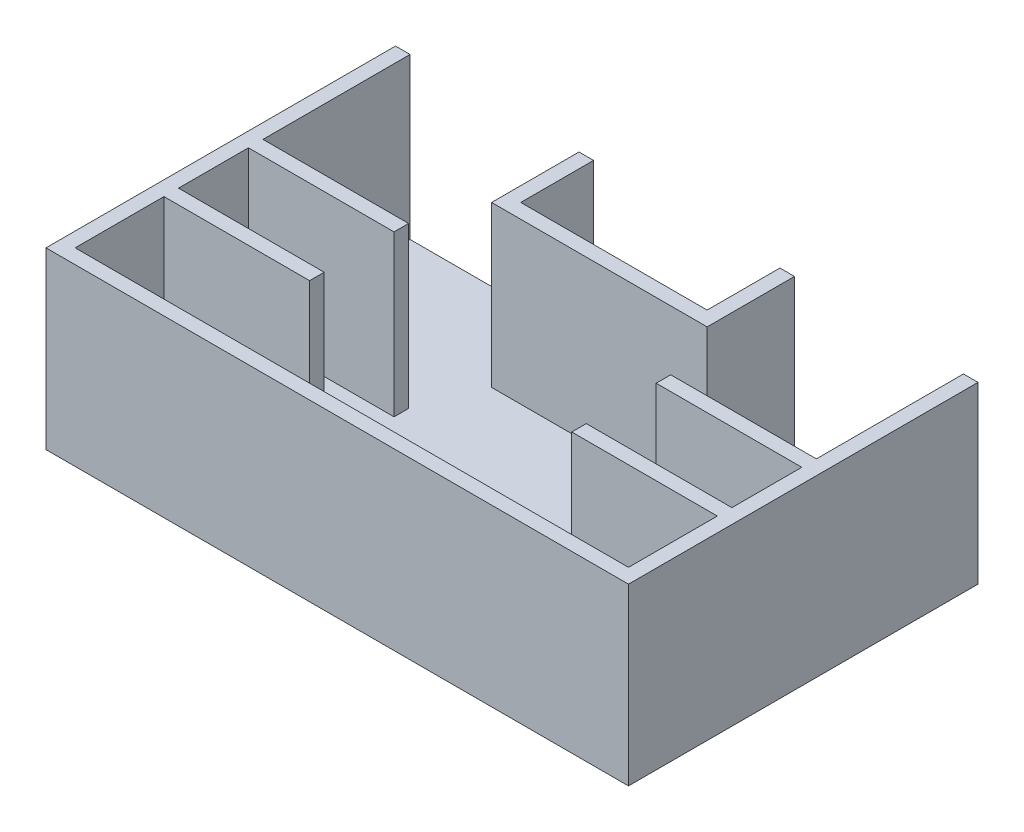
SolidWorks part; units mm, degrees
ref_plane "Front Plane" through (0, 0, 0) normal (0, 0, 1) x (1, 0, 0)
ref_plane "Top Plane" through (0, 0, 0) normal (0, 1, 0) x (1, 0, 0)
ref_plane "Right Plane" through (0, 0, 0) normal (1, 0, 0) x (0, 0, -1)
sketch "Sketch2" plane through (0, 0, 0) normal (0, 1, 0) x (1, 0, 0)
  line L1 (50, 50) -> (-50, 50)
  line L2 (50, 50) -> (50, -50)
  line L3 (50, -50) -> (-50, -50)
  line L4 (-50, 50) -> (-50, -50)
  line L5 (50, 50) -> (-50, -50) construction
  line L6 (50, -50) -> (-50, 50) construction
  point P0 (0, 0)
  dimension "D1" = 100
  dimension "D2" = 100
extrude "Boss-Extrude1" add sketch "Sketch2" along normal blind 2.5
sketch "Sketch4" plane through (0, 2.5, 0) normal (0, 1, 0) x (1, 0, 0)
  line L0 (-22.5, -17.75) -> (-22.5, -29.75) construction
  line L1 (-47.5, -47.5) -> (47.5, -47.5)
  line L2 (-47.5, -47.5) -> (-47.5, -32.25)
  line L3 (-47.5, 47.5) -> (-18.5, 47.5)
  line L4 (47.5, -47.5) -> (47.5, -32.25)
  line L5 (-47.5, 47.5) -> (47.5, -47.5) construction
  line L6 (-47.5, -23.75) -> (47.5, -23.75) construction
  line L7 (-47.5, -15.25) -> (-22.5, -15.25)
  line L8 (-47.5, -17.75) -> (-22.5, -17.75)
  line L9 (-22.5, -15.25) -> (-22.5, -17.75)
  line L10 (-22.5, -29.75) -> (-47.5, -29.75)
  line L11 (-22.5, -29.75) -> (-22.5, -32.25)
  line L12 (-50, 50) -> (-50, -50)
  line L13 (-50, -50) -> (50, -50)
  line L14 (50, -50) -> (50, 50)
  line L15 (50, 50) -> (-50, 50)
  line L16 (-50, 50) -> (-50, -50)
  line L17 (-50, -50) -> (50, -50)
  line L18 (50, -50) -> (50, 50)
  line L19 (50, 50) -> (16, 50)
  line L20 (-22.5, -32.25) -> (-47.5, -32.25)
  line L21 (-47.5, -29.75) -> (-47.5, -17.75)
  line L22 (-47.5, -15.25) -> (-47.5, 47.5)
  line L23 (0, -50) -> (0, 75) construction
  line L24 (47.5, -17.75) -> (22.5, -17.75)
  line L25 (47.5, -15.25) -> (22.5, -15.25)
  line L26 (22.5, -15.25) -> (22.5, -17.75)
  line L27 (22.5, -29.75) -> (47.5, -29.75)
  line L28 (22.5, -29.75) -> (22.5, -32.25)
  line L29 (22.5, -32.25) -> (47.5, -32.25)
  line L30 (47.5, -29.75) -> (47.5, -17.75)
  line L31 (47.5, -15.25) -> (47.5, 47.5)
  line L32 (-16, 47.5) -> (-16, -2.5)
  line L33 (-16, -2.5) -> (16, -2.5)
  line L34 (16, -2.5) -> (16, 47.5)
  line L35 (18.5, 47.5) -> (47.5, 47.5)
  line L36 (18.5, 47.5) -> (18.5, -5)
  line L37 (18.5, -5) -> (-18.5, -5)
  line L38 (-18.5, -5) -> (-18.5, 47.5)
  line L41 (-16, 47.5) -> (-16, 50)
  line L42 (16, 47.5) -> (16, 50)
  line L43 (-16, 50) -> (-50, 50)
  point P0 (0, 0)
  point P12 (-22.5, -23.75)
  point P33 (0, -2.5)
  point P36 (0, 0)
  dimension "D1" = 95
  dimension "D2" = 95
  dimension "D4" = 23.75
  dimension "D5" = 12
  dimension "D6" = 25
  dimension "D7" = 2.5
  dimension "D8" = 2.5
  dimension "D9" = 32
  dimension "D10" = 50
  dimension "D11" = 2.5
  dimension "D12" = 2.5
  dimension "D13" = 2.5
  dimension "D3" = 0
extrude "Boss-Extrude2" add sketch "Sketch4" along normal blind 27.5
sketch "Sketch5" plane through (50, 0, 0) normal (1, 0, 0) x (0, 0, -1)
  line L1 (10, 30) -> (10, 0)
  line L3 (-50, 30) -> (50, 30) construction
  line L5 (10, 30) -> (50, 30)
  line L6 (50, 30) -> (50, 0)
  line L7 (-50, 0) -> (50, 0) construction
  line L8 (10, 0) -> (50, 0)
  dimension "D1" = 40
sketch "Sketch9" plane through (0, 2.5, 0) normal (0, 1, 0) x (1, 0, 0)
  line L0 (-16, -2.5) -> (16, -2.5)
  line L1 (16, -2.5) -> (16, 50)
  line L2 (16, 50) -> (-16, 50)
  line L3 (-50, 50) -> (50, 50) construction
  line L4 (-16, 50) -> (-16, -2.5)
  line L5 (50, 50) -> (16, 50) construction
  point P2 (0, 0)
extrude "Cut-Extrude3" cut sketch "Sketch9" against normal up to surface (2.5 mm away) up to face at (0, 0, 0)
extrude "Cut-Extrude4" cut sketch "Sketch5" against normal up to surface (100 mm away) up to face at (-50, 15, 0)
equation "\"T\"= 2.5mm"
equation "\"D1@Boss-Extrude1\"=\"T\""
equation "\"D1@Sketch4\"=\"Length\"-2*\"T\""
equation "\"D2@Sketch4\"=\"Width\"-2*\"T\""
equation "\"D4@Sketch4\"=(\"Length\"-2*\"T\") / 4"
equation "\"Width\"= 100mm"
equation "\"D7@Sketch4\"=\"T\""
equation "\"D8@Sketch4\"=\"T\""
equation "\"Spinner_Radius\"= 20mm"
equation "\"D10@Sketch4\"=50"
equation "\"D11@Sketch4\"=\"T\""
equation "\"D12@Sketch4\"=\"T\""
equation "\"D13@Sketch4\"=\"T\""
equation "\"Length\"= 100mm"
equation "\"D1@Sketch2\"=\"Length\""
equation "\"D2@Sketch2\"=\"Width\""
equation "\"Height\"= 30mm"
equation "\"D1@Boss-Extrude2\"=\"Height\"-\"T\""
